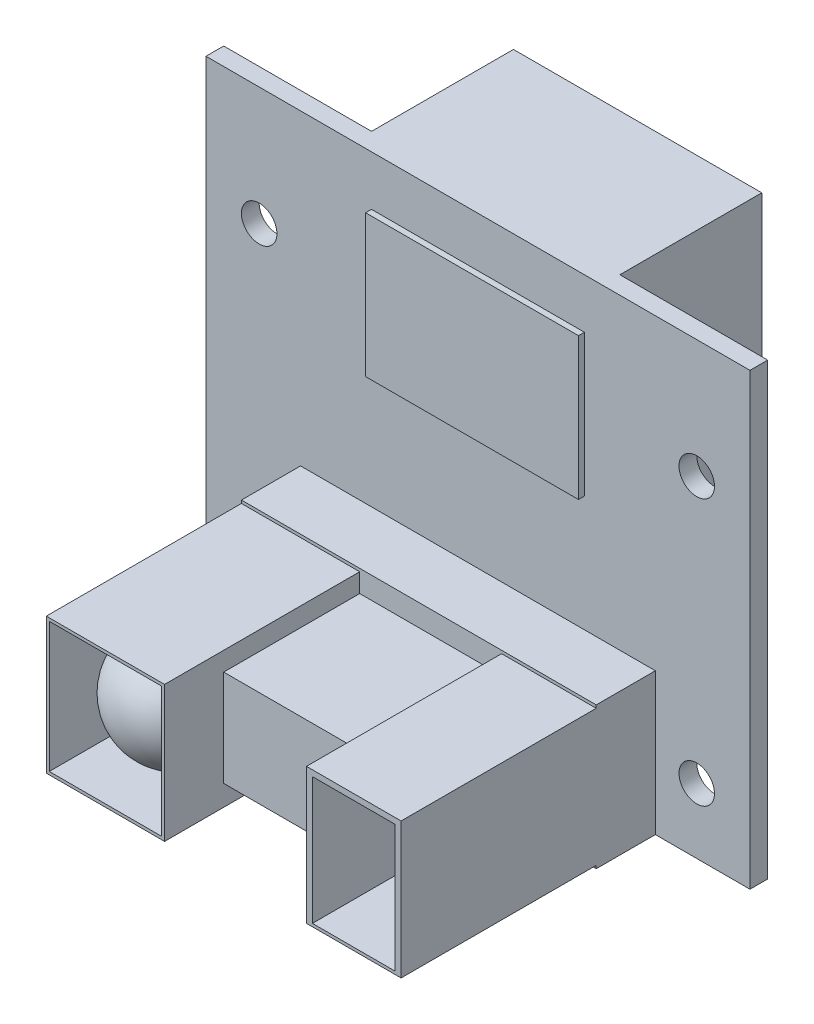
SolidWorks part; units mm, degrees
ref_plane "Front Plane" through (0, 0, 0) normal (0, 0, 1) x (1, 0, 0)
ref_plane "Top Plane" through (0, 0, 0) normal (0, 1, 0) x (1, 0, 0)
ref_plane "Right Plane" through (0, 0, 0) normal (1, 0, 0) x (0, 0, -1)
ref_plane "Plane1" through (0, 0, 0) normal (0, 0, 1) x (1, 0, 0)
ref_plane "Plane2" through (0, 0, 0) normal (0, 1, 0) x (1, 0, 0)
ref_plane "Plane3" through (0, 0, 0) normal (1, 0, 0) x (0, 0, -1)
ref_plane "Plane7" through (0, 0, 17) normal (0, 0, 1) x (1, 0, 0)
ref_plane "Plane14" through (0, 0, 12) normal (0, 0, 1) x (1, 0, 0)
sketch "Sketch2" plane through (0, 0, 0) normal (0, 0, 1) x (1, 0, 0)
  line L1 (0, 0) -> (46, 0)
  line L2 (0, 0) -> (0, 38)
  line L3 (0, 38) -> (46, 38)
  line L4 (46, 0) -> (46, 38)
  circle A0 centre (4.5, 28) radius 1.5
  circle A1 centre (4.5, 5.5) radius 1.5
  circle A2 centre (41.5, 5.5) radius 1.5
  circle A3 centre (41.5, 28) radius 1.5
  dimension "D3" = 3
  dimension "D4" = 22.5
  dimension "D5" = 22.5
  dimension "D7" = 4.5
  dimension "D8" = 10
  dimension "D9" = 10
  dimension "D1" = 46
  dimension "D2" = 38
  dimension "D6" = 4.5
extrude "Boss-Extrude1" add sketch "Sketch2" along normal blind 1.5
sketch "Sketch12" plane through (0, 0, 0) normal (0, 0, 1) x (1, 0, 0)
  line L0 (46, 38) -> (0, 38) construction
  line L1 (33.5, 38) -> (12.5, 38)
  line L2 (33.5, 38) -> (33.5, 18)
  line L3 (33.5, 18) -> (12.5, 18)
  line L4 (12.5, 38) -> (12.5, 18)
  line L5 (0, -55) -> (0, 55) construction
  dimension "D1" = 21
  dimension "D2" = 12.5
  dimension "D3" = 20
extrude "Boss-Extrude6" add sketch "Sketch12" against normal blind 12
sketch "Sketch13" plane through (0, 0, 0) normal (0, 0, 1) x (1, 0, 0)
  line L1 (14, 33.7891) -> (32, 33.7891)
  line L2 (14, 33.7891) -> (14, 21.7891)
  line L3 (14, 21.7891) -> (32, 21.7891)
  line L4 (32, 33.7891) -> (32, 21.7891)
  line L5 (46, 0) -> (46, 38) construction
  dimension "D1" = 12
  dimension "D2" = 18
  dimension "D3" = 14
extrude "Boss-Extrude7" add sketch "Sketch13" along normal blind 2
sketch "Sketch15" plane through (0, 0, 0) normal (0, 0, 1) x (1, 0, 0)
  line L1 (8, 12) -> (38, 12)
  line L2 (8, 12) -> (8, 0)
  line L3 (8, 0) -> (38, 0)
  line L4 (38, 12) -> (38, 0)
  line L6 (0, 0) -> (46, 0) construction
  line L7 (46, 0) -> (46, 38) construction
  dimension "D1" = 30
  dimension "D2" = 12
  dimension "D3" = 0
  dimension "D4" = 8
extrude "Boss-Extrude8" add sketch "Sketch15" along normal blind 6.5
sketch "Sketch16" plane through (0, 0, 0) normal (0, 0, 1) x (1, 0, 0)
  line L0 (38, 12) -> (8, 12) construction
  line L1 (8, 11.75) -> (18, 11.75)
  line L2 (8, 11.75) -> (8, 0.25)
  line L3 (8, 0.25) -> (18, 0.25)
  line L4 (18, 11.75) -> (18, 0.25)
  line L5 (55, 0) -> (-55, 0) construction
  line L6 (8, 12) -> (8, 0) construction
  dimension "D1" = 10
  dimension "D2" = 0.25
  dimension "D3" = 0.25
  dimension "D4" = 0
extrude "Boss-Extrude9" add sketch "Sketch16" along normal blind 23
sketch "Sketch17" plane through (0, 0, 0) normal (0, 0, 1) x (1, 0, 0)
  line L0 (38, 0) -> (38, 12) construction
  line L1 (38, 11.75) -> (30, 11.75)
  line L2 (38, 11.75) -> (38, 0.25)
  line L3 (38, 0.25) -> (30, 0.25)
  line L4 (30, 11.75) -> (30, 0.25)
  line L5 (38, 12) -> (8, 12) construction
  line L6 (55, 0) -> (-55, 0) construction
  dimension "D1" = 0.25
  dimension "D2" = 8
  dimension "D3" = 0.25
extrude "Boss-Extrude10" add sketch "Sketch17" along normal blind 23
sketch "Sketch18" plane through (0, 0, 0) normal (0, 0, 1) x (1, 0, 0)
  line L0 (18, 11.75) -> (18, 0.25) construction
  line L1 (18, 10.1516) -> (30, 10.1516)
  line L2 (18, 10.1516) -> (18, 2)
  line L3 (18, 2) -> (30, 2)
  line L4 (30, 10.1516) -> (30, 2)
  line L5 (30, 11.75) -> (30, 0.25) construction
  line L6 (55, 0) -> (-55, 0) construction
  dimension "D1" = 2
extrude "Boss-Extrude11" add sketch "Sketch18" along normal blind 18
sketch "Sketch19" plane through (0, 0, 17) normal (0, 0, 1) x (1, 0, 0)
  line L0 (18, 0.25) -> (18, 11.75) construction
  line L1 (8.25, 11.5) -> (17.75, 11.5)
  line L2 (8.25, 11.5) -> (8.25, 0.5)
  line L3 (8.25, 0.5) -> (17.75, 0.5)
  line L4 (17.75, 11.5) -> (17.75, 0.5)
  line L5 (38, 12) -> (8, 12) construction
  line L6 (8, 11.75) -> (8, 0.25) construction
  line L7 (55, 0) -> (-55, 0) construction
  dimension "D1" = 0.25
  dimension "D2" = 0.5
  dimension "D3" = 0.25
  dimension "D4" = 0.5
extrude "Cut-Extrude3" cut sketch "Sketch19" along normal blind 16.5
sketch "Sketch21" plane through (0, 0, 17) normal (0, 0, 1) x (1, 0, 0)
  line L0 (13, 5.6178) -> (13, 17.7322) construction
  line L4 (8.25, 11.5) -> (8.25, 0.5) construction
  circle A0 centre (13, 5.6178) radius 4.75
  dimension "D1" = 9.5
surface "Surface-Revolve3" sketch "Sketch21" parameters "D1"=360
sketch "Sketch22" plane through (0, 0, 12) normal (0, 0, 1) x (1, 0, 0)
  line L0 (30, 11.75) -> (38, 11.75) construction
  line L1 (30.5, 11.25) -> (37.5, 11.25)
  line L2 (30.5, 11.25) -> (30.5, 0.5)
  line L3 (30.5, 0.5) -> (37.5, 0.5)
  line L4 (37.5, 11.25) -> (37.5, 0.5)
  line L5 (19.25, 0) -> (-19.25, 0) construction
  line L6 (38, 0.25) -> (38, 11.75) construction
  line L7 (30, 11.75) -> (30, 0.25) construction
  point P6 (34, 11.75)
  dimension "D1" = 0.5
  dimension "D2" = 0.5
  dimension "D3" = 0.5
  dimension "D4" = 0.5
extrude "Cut-Extrude4" cut sketch "Sketch22" along normal blind 16.5
sketch "Sketch23" plane through (0, 0, 12) normal (0, 0, 1) x (1, 0, 0)
  line L0 (30.5, 11.25) -> (30.5, 0.5) construction
  line L1 (34, 5.9559) -> (34, 14.7922) construction
  circle A0 centre (34, 5.9559) radius 3.5
  dimension "D1" = 7
surface "Surface-Revolve4" sketch "Sketch23" parameters "D1"=360
